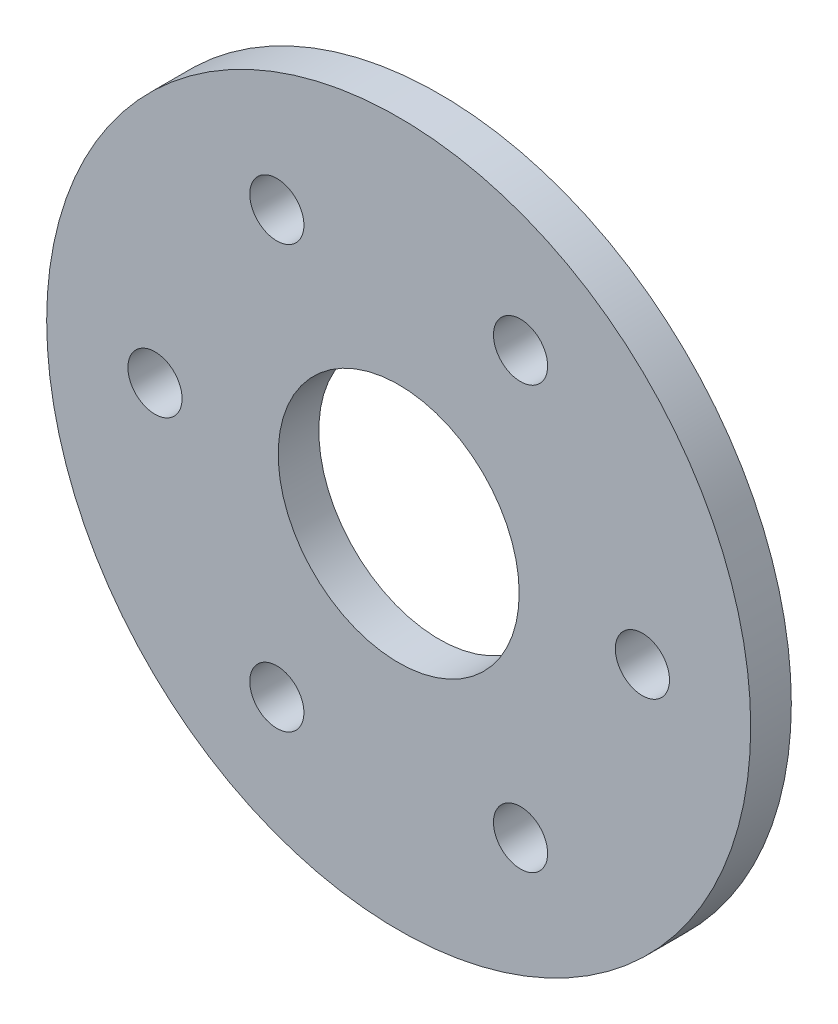
SolidWorks part; units mm, degrees
material "Resina de melamina"
ref_plane "Alzado" through (0, 0, 0) normal (0, 0, 1) x (1, 0, 0)
ref_plane "Planta" through (0, 0, 0) normal (0, 1, 0) x (1, 0, 0)
ref_plane "Vista lateral" through (0, 0, 0) normal (1, 0, 0) x (0, 0, -1)
sketch "Croquis1" plane through (0, 0, 0) normal (0, 0, 1) x (1, 0, 0)
  line L0 (0, 0) -> (-18, 0) construction
  circle A0 centre (0, 0) radius 26
  circle A1 centre (-18, 0) radius 2
  circle A2 centre (0, 0) radius 26
  circle A3 centre (-9, 15.5885) radius 2
  circle A4 centre (0, 0) radius 26
  circle A5 centre (9, 15.5885) radius 2
  circle A6 centre (0, 0) radius 26
  circle A7 centre (18, 0) radius 2
  circle A8 centre (0, 0) radius 26
  circle A9 centre (9, -15.5885) radius 2
  circle A10 centre (0, 0) radius 26
  circle A11 centre (-9, -15.5885) radius 2
  circle A12 centre (0, 0) radius 8.9
  dimension "D2" = 4
  dimension "D4" = 52
  dimension "D5" = 17.8
  dimension "D1" = 18
  dimension "D3" = 6
extrude "Saliente-Extruir1" add sketch "Croquis1" along normal blind 3
